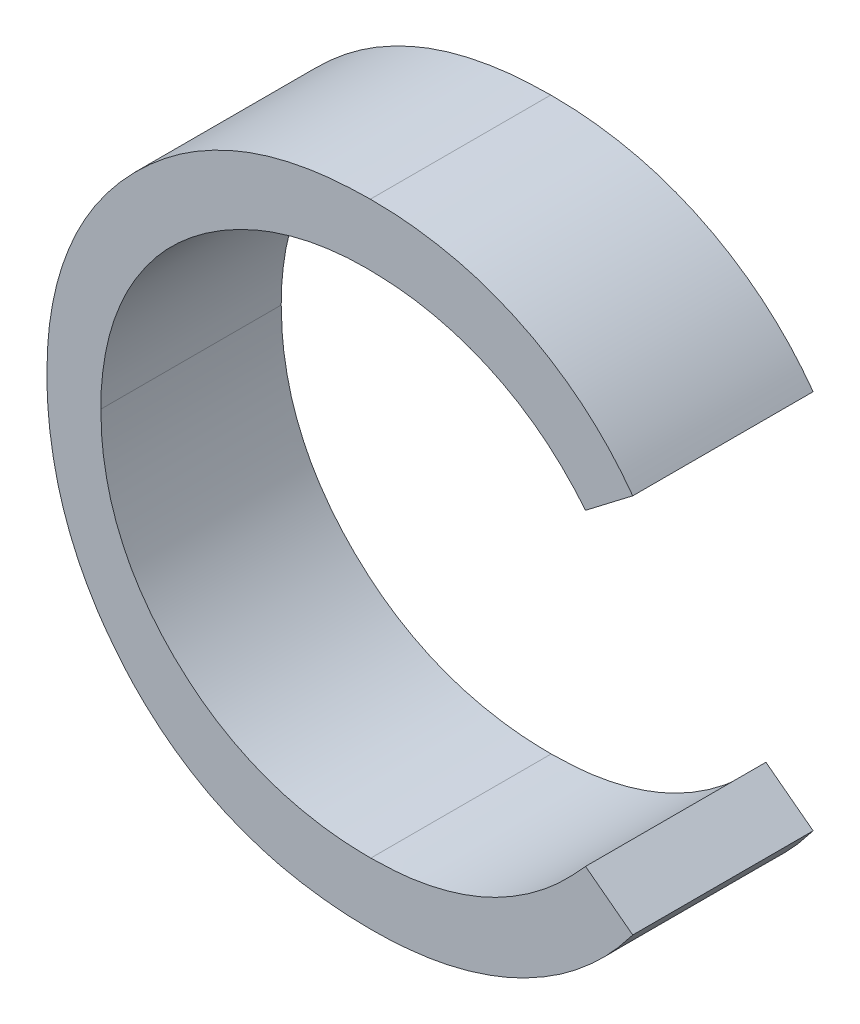
SolidWorks part; units mm, degrees
ref_plane "Plan de face" through (0, 0, 0) normal (0, 0, 1) x (1, 0, 0)
ref_plane "Plan de dessus" through (0, 0, 0) normal (0, 1, 0) x (1, 0, 0)
ref_plane "Plan de droite" through (0, 0, 0) normal (1, 0, 0) x (0, 0, -1)
sketch "Esquisse1" plane through (0, 0, 0) normal (0, 0, 1) x (1, 0, 0)
  text T0 "C" font "Century Gothic" height 5
extrude "Boss.-Extru.1" add sketch "Esquisse1" along normal blind 1.5
